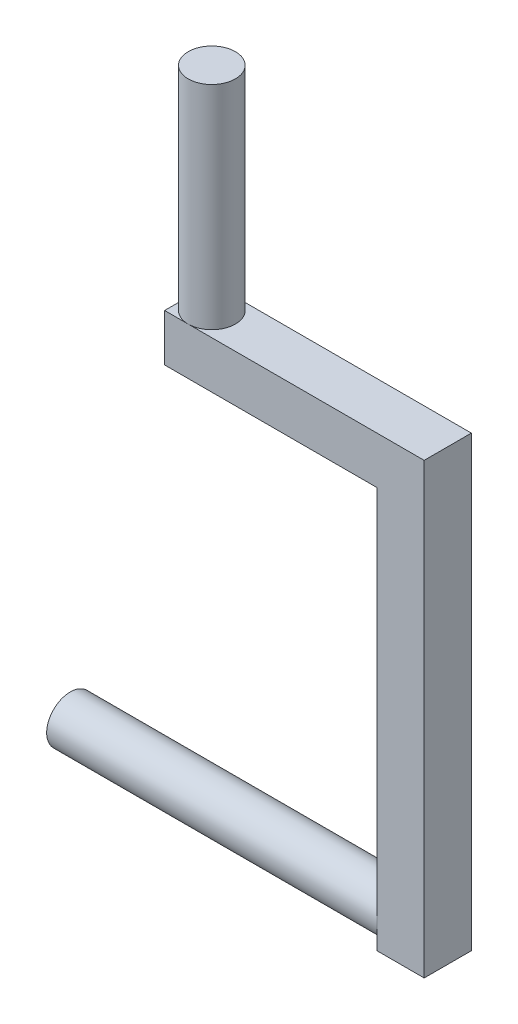
SolidWorks part; units mm, degrees
ref_plane "Front Plane" through (0, 0, 0) normal (0, 0, 1) x (1, 0, 0)
ref_plane "Top Plane" through (0, 0, 0) normal (0, 1, 0) x (1, 0, 0)
ref_plane "Right Plane" through (0, 0, 0) normal (1, 0, 0) x (0, 0, -1)
sketch "Sketch2" plane through (0, 0, 0) normal (0, 1, 0) x (1, 0, 0)
  circle A0 centre (0, 0) radius 6.35
extrude "Boss-Extrude1" add sketch "Sketch2" against normal blind 57.15
sketch "Sketch4" plane through (0, -57.15, 0) normal (0, -1, 0) x (1, 0, 0)
  line L0 (0, 0) -> (57.15, 0) construction
  line L2 (63.5, -6.35) -> (-6.35, -6.35)
  line L3 (63.5, -6.35) -> (63.5, 6.35)
  line L4 (63.5, 6.35) -> (-6.35, 6.35)
  line L5 (-6.35, -6.35) -> (-6.35, 6.35)
  line L6 (63.5, -6.35) -> (-6.35, 6.35) construction
  line L7 (63.5, 6.35) -> (-6.35, -6.35) construction
  point P0 (0, 0)
  point P5 (28.575, 0)
  point P10 (0, 0)
  dimension "D1" = 57.15
  dimension "D2" = 69.85
  dimension "D3" = 12.7
extrude "Boss-Extrude6" add sketch "Sketch4" along normal blind 12.7 contours L3 L4 L5 L2
sketch "Sketch7" plane through (0, -69.85, 0) normal (0, -1, 0) x (1, 0, 0)
  line L0 (63.5, -6.35) -> (63.5, 6.35) construction
  line L1 (63.5, 6.35) -> (-6.35, 6.35) construction
  point P0 (57.15, 0)
  dimension "D1" = 6.35
  dimension "D2" = 6.35
sketch "Sketch8" plane through (0, -69.85, 0) normal (0, -1, 0) x (1, 0, 0)
  line L0 (63.5, 6.35) -> (-6.35, 6.35) construction
  line L1 (63.5, -6.35) -> (50.8, -6.35)
  line L2 (63.5, -6.35) -> (63.5, 6.35)
  line L3 (63.5, 6.35) -> (50.8, 6.35)
  line L4 (50.8, -6.35) -> (50.8, 6.35)
  line L5 (63.5, -6.35) -> (50.8, 6.35) construction
  line L6 (63.5, 6.35) -> (50.8, -6.35) construction
  point P0 (57.15, 0)
  dimension "D1" = 12.7
extrude "Boss-Extrude7" add sketch "Sketch8" along normal blind 107.95
sketch "Sketch9" plane through (50.8, 0, 0) normal (-1, 0, 0) x (0, 0, 1)
  line L0 (6.35, -177.8) -> (-6.35, -177.8) construction
  line L1 (6.35, -177.8) -> (6.35, -69.85) construction
  circle A0 centre (0, -171.45) radius 6.35
  point P0 (0, -171.45)
  dimension "D1" = 6.35
  dimension "D2" = 6.35
extrude "Boss-Extrude8" add sketch "Sketch9" along normal blind 88.9
